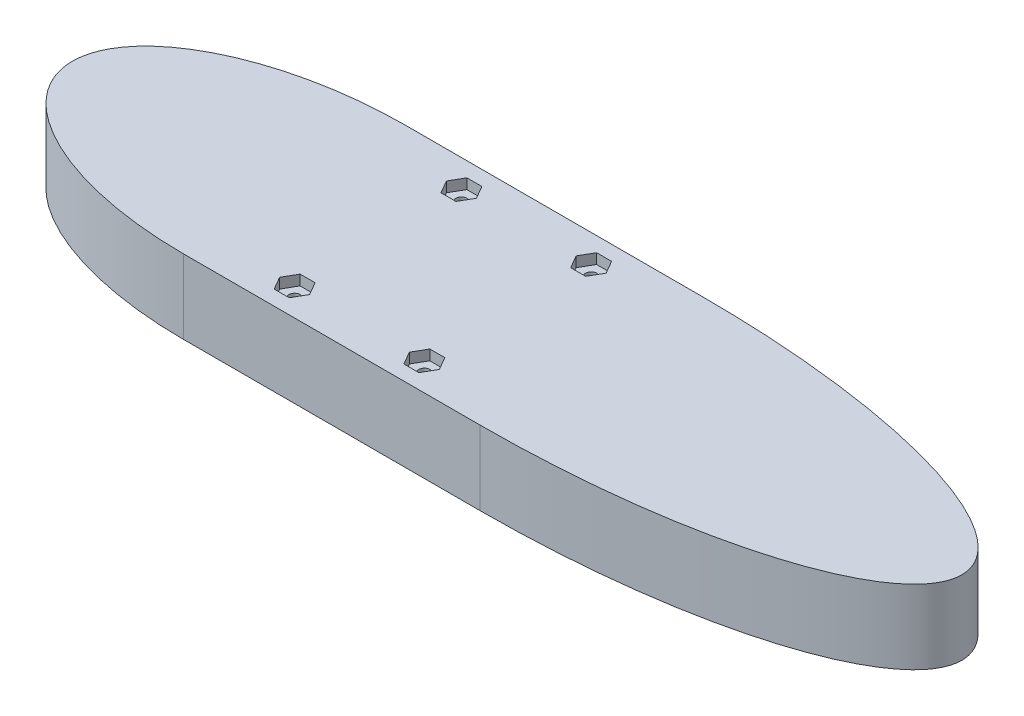
SolidWorks part; units mm, degrees
ref_plane "Front Plane" through (0, 0, 0) normal (0, 0, 1) x (1, 0, 0)
ref_plane "Top Plane" through (0, 0, 0) normal (0, 1, 0) x (1, 0, 0)
ref_plane "Right Plane" through (0, 0, 0) normal (1, 0, 0) x (0, 0, -1)
sketch "Sketch1" plane through (0, 0, 0) normal (0, 1, 0) x (1, 0, 0)
  line L1 (76.2, 38.1) -> (177.8, 38.1)
  line L3 (76.2, -38.1) -> (177.8, -38.1)
  ellipse E0 centre (76.2, 0) end of major axis (0, 0) minor radius 38.1 (76.2, 38.1) -> (76.2, -38.1) ccw
  ellipse E1 centre (177.8, 0) end of major axis (304.8, 0) minor radius 38.1 (177.8, -38.1) -> (177.8, 38.1) ccw
  point P0 (0, 0)
  dimension "D1" = 101.6
  dimension "D2" = 76.2
  dimension "D3" = 127
  dimension "D4" = 76.2
extrude "Boss-Extrude1" add sketch "Sketch1" along normal blind 25.4
sketch "Sketch2" plane through (0, 0, 0) normal (1, 0, 0) x (0, 0, -1)
  line L2 (-38.1, 25.4) -> (-38.1, 0) construction
  line L3 (-38.1, 0) -> (38.1, 0) construction
  circle A0 centre (0, 93.3971) radius 57.15
  point P5 (-38.1, 50.8)
  dimension "D1" = 114.3
  dimension "D2" = 50.8
extrude "Cut-Extrude2" [suppressed] cut sketch "Sketch2" along normal through all
sketch "Sketch3" plane through (0, 0, 0) normal (0, -1, 0) x (1, 0, 0)
  line L1 (152.4, -61.0376) -> (-25.885, -61.0376)
  line L2 (152.4, -61.0376) -> (152.4, 51.2506)
  line L3 (152.4, 51.2506) -> (-25.885, 51.2506)
  line L4 (-25.885, -61.0376) -> (-25.885, 51.2506)
  line L5 (152.4, -61.0376) -> (-25.885, 51.2506) construction
  line L6 (152.4, 51.2506) -> (-25.885, -61.0376) construction
  point P0 (63.2575, -4.8935)
  dimension "D1" = 152.4
extrude "Cut-Extrude3" [suppressed] cut sketch "Sketch3" against normal through all
sketch "Sketch4" plane through (0, 0, 0) normal (0, -1, 0) x (1, 0, 0)
  line L0 (177.8, -38.1) -> (76.2, -38.1) construction
  line L1 (139.7, -38.1) -> (76.2, -38.1)
  line L2 (139.7, -38.1) -> (139.7, 38.1)
  line L3 (139.7, 38.1) -> (76.2, 38.1)
  line L4 (76.2, -38.1) -> (76.2, 38.1)
  line L5 (139.7, -38.1) -> (76.2, 38.1) construction
  line L6 (139.7, 38.1) -> (76.2, -38.1) construction
  point P0 (107.95, 0)
  dimension "D1" = 63.5
extrude "Cut-Extrude4" cut sketch "Sketch4" against normal blind 0.01
hole_wizard "#6 Clearance Hole1" positions "Sketch5" profile "Sketch6" hole size "#6" standard "ANSI Inch" end condition through all
sketch "Sketch5" plane through (0, 25.4, 0) normal (0, 1, 0) x (1, 0, 0)
  line L0 (104.775, 28.575) -> (104.775, -28.575) construction
  line L3 (76.2, -38.1) -> (177.8, -38.1) construction
  point P0 (104.775, 28.575)
  point P2 (149.225, 28.575)
  point P4 (149.225, -28.575)
  point P6 (104.775, -28.575)
  dimension "D1" = 44.45
  dimension "D2" = 57.15
  dimension "D3" = 28.575
  dimension "D4" = 9.525
sketch "Sketch6" plane through (104.775, 25.4, -28.575) normal (1, 0, 0) x (0, 0, 1)
  line L0 (0, 0) -> (0, 25.4)
  line L1 (0, 25.4) -> (1.8986, 25.4)
  line L2 (1.8986, 25.4) -> (1.8986, 0)
  line L5 (1.8986, 0) -> (0, 0)
  line L11 (0, -6.35) -> (0, 107.95) construction
  dimension "Thru Hole Dia." = 3.7973
  dimension "Thru Hole Depth" = 25.4
sketch "Sketch7" plane through (0, 25.4, 0) normal (0, 1, 0) x (1, 0, 0)
  line L1 (144.0924, 28.575) -> (146.6587, 24.13)
  line L2 (146.6587, 24.13) -> (151.7913, 24.13)
  line L3 (151.7913, 24.13) -> (154.3576, 28.575)
  line L4 (154.3576, 28.575) -> (151.7913, 33.02)
  line L5 (151.7913, 33.02) -> (146.6587, 33.02)
  line L6 (146.6587, 33.02) -> (144.0924, 28.575)
  line L7 (144.0924, -28.575) -> (146.6587, -33.02)
  line L8 (146.6587, -33.02) -> (151.7913, -33.02)
  line L9 (151.7913, -33.02) -> (154.3576, -28.575)
  line L10 (154.3576, -28.575) -> (151.7913, -24.13)
  line L11 (151.7913, -24.13) -> (146.6587, -24.13)
  line L12 (146.6587, -24.13) -> (144.0924, -28.575)
  line L13 (99.6424, -28.575) -> (102.2087, -33.02)
  line L14 (102.2087, -33.02) -> (107.3413, -33.02)
  line L15 (107.3413, -33.02) -> (109.9076, -28.575)
  line L16 (109.9076, -28.575) -> (107.3413, -24.13)
  line L17 (107.3413, -24.13) -> (102.2087, -24.13)
  line L18 (102.2087, -24.13) -> (99.6424, -28.575)
  line L19 (99.6424, 28.575) -> (102.2087, 24.13)
  line L20 (102.2087, 24.13) -> (107.3413, 24.13)
  line L21 (107.3413, 24.13) -> (109.9076, 28.575)
  line L22 (109.9076, 28.575) -> (107.3413, 33.02)
  line L23 (107.3413, 33.02) -> (102.2087, 33.02)
  line L24 (102.2087, 33.02) -> (99.6424, 28.575)
  circle A0 centre (149.225, 28.575) radius 4.445 construction
  circle A1 centre (149.225, -28.575) radius 4.445 construction
  circle A2 centre (104.775, -28.575) radius 4.445 construction
  circle A3 centre (104.775, 28.575) radius 4.445 construction
  dimension "D1" = 8.89
  dimension "D2" = 8.89
  dimension "D3" = 8.89
  dimension "D4" = 8.89
extrude "Cut-Extrude5" cut sketch "Sketch7" against normal blind 3.5052
ref_plane "Plane1" through (0, 12.7, 0) normal (0, 1, 0) x (1, 0, 0)
